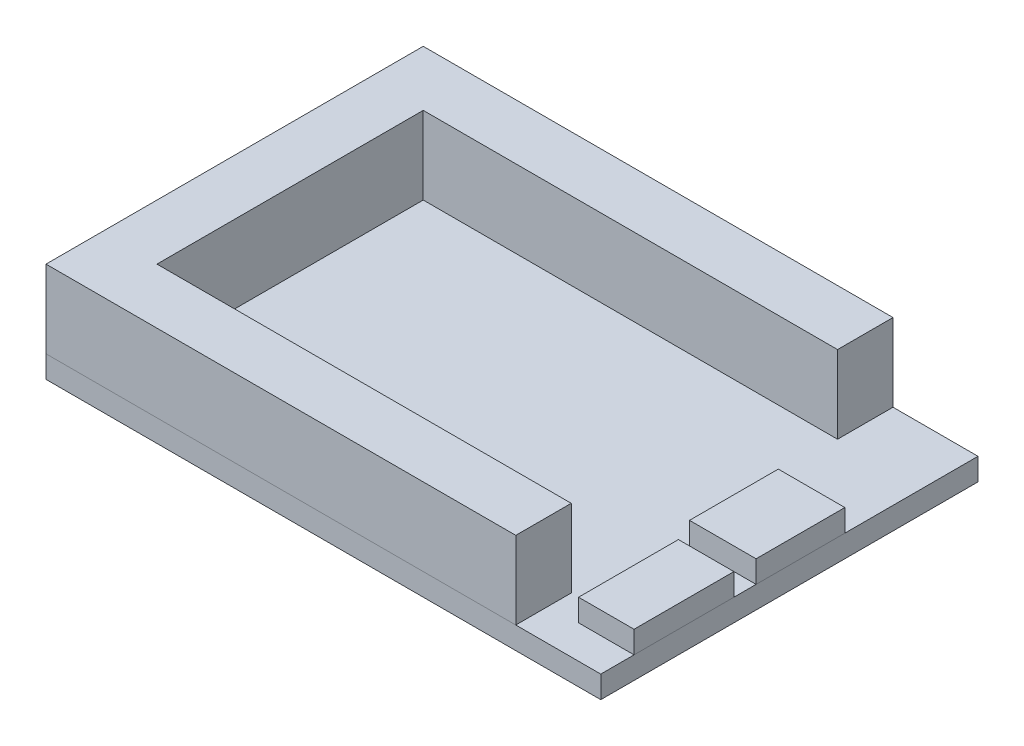
SolidWorks part; units mm, degrees
ref_plane "前视基准面" through (0, 0, 0) normal (0, 0, 1) x (1, 0, 0)
ref_plane "上视基准面" through (0, 0, 0) normal (0, 1, 0) x (1, 0, 0)
ref_plane "右视基准面" through (0, 0, 0) normal (1, 0, 0) x (0, 0, -1)
other "Configuration Table"
sketch "草图1" plane through (0, 0, 0) normal (0, 1, 0) x (1, 0, 0)
  line L1 (-25, -17) -> (25, -17)
  line L2 (-25, -17) -> (-25, 17)
  line L3 (-25, 17) -> (25, 17)
  line L4 (25, -17) -> (25, 17)
  line L5 (-25, -17) -> (25, 17) construction
  line L6 (-25, 17) -> (25, -17) construction
  point P0 (0, 0)
  dimension "D1" = 50
  dimension "D2" = 34
extrude "凸台-拉伸1" add sketch "草图1" along normal blind 2 contours L3 L4 L1 L2
sketch "草图2" plane through (0, 2, 0) normal (0, 1, 0) x (1, 0, 0)
  line L0 (25, -17) -> (25, 17) construction
  line L1 (19, 5) -> (25, 5)
  line L2 (19, 5) -> (19, -3)
  line L3 (19, -3) -> (25, -3)
  line L4 (25, 5) -> (25, -3)
  line L5 (19, 5) -> (25, -3) construction
  line L6 (19, -3) -> (25, 5) construction
  line L7 (-25, 17) -> (25, 17) construction
  line L8 (-25, -17) -> (25, -17) construction
  line L9 (25, -5) -> (20, -5)
  line L10 (25, -5) -> (25, -14)
  line L11 (25, -14) -> (20, -14)
  line L12 (20, -5) -> (20, -14)
  line L13 (25, -5) -> (20, -14) construction
  line L14 (25, -14) -> (20, -5) construction
  point P0 (22, 1)
  point P9 (22.5, -9.5)
  point P16 (0, 0)
  dimension "D1" = 6
  dimension "D2" = 12
  dimension "D3" = 8
  dimension "D4" = 5
  dimension "D5" = 3
  dimension "D6" = 9
extrude "凸台-拉伸2" add sketch "草图2" along normal blind 2 separate body
sketch "草图3" plane through (0, 2, 0) normal (0, 1, 0) x (1, 0, 0)
  line L0 (17.3404, 12) -> (-20, 12)
  line L1 (-20, 12) -> (-20, -12)
  line L2 (-20, -12) -> (17.3404, -12)
  line L3 (17.3404, -12) -> (17.3404, -17)
  line L4 (-25, 17) -> (-25, -17)
  line L5 (-25, -17) -> (25, -17)
  line L6 (25, -17) -> (25, 17)
  line L7 (25, 17) -> (-25, 17)
  line L8 (-25, 17) -> (-25, -17)
  line L9 (-25, -17) -> (17.3404, -17)
  line L11 (17.3404, 17) -> (-25, 17)
  line L12 (17.3404, 12) -> (17.3404, 17)
  dimension "D2" = 5
  dimension "D3" = 5
  dimension "D1" = 0
extrude "凸台-拉伸3" add sketch "草图3" along normal blind 7 separate body
